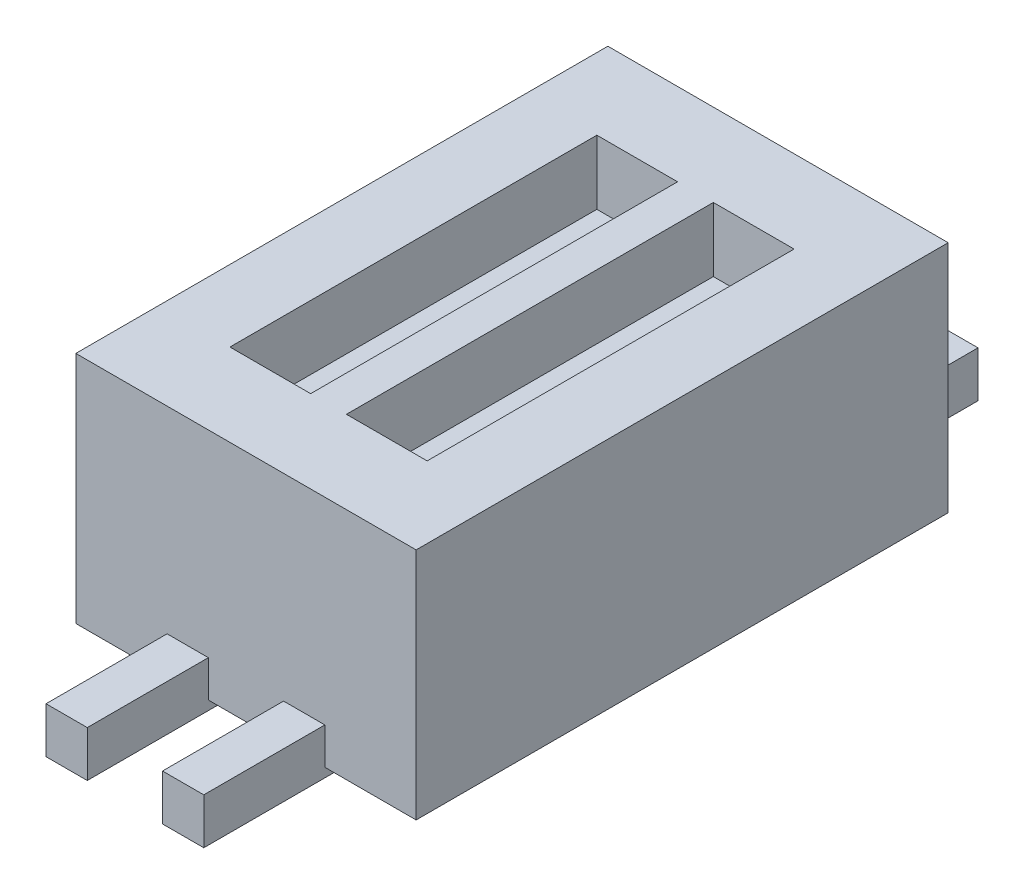
SolidWorks part; units mm, degrees
ref_plane "Front Plane" through (0, 0, 0) normal (0, 0, 1) x (1, 0, 0)
ref_plane "Top Plane" through (0, 0, 0) normal (0, 1, 0) x (1, 0, 0)
ref_plane "Right Plane" through (0, 0, 0) normal (1, 0, 0) x (0, 0, -1)
sketch "Sketch1" plane through (0, 0, 0) normal (0, 1, 0) x (1, 0, 0)
  line L1 (-1.855, 2.9) -> (1.855, 2.9)
  line L2 (-1.855, 2.9) -> (-1.855, -2.9)
  line L3 (-1.855, -2.9) -> (1.855, -2.9)
  line L4 (1.855, 2.9) -> (1.855, -2.9)
  line L5 (-1.855, 2.9) -> (1.855, -2.9) construction
  line L6 (-1.855, -2.9) -> (1.855, 2.9) construction
  point P0 (0, 0)
  dimension "D1" = 5.8
  dimension "D2" = 3.71
extrude "Boss-Extrude1" add sketch "Sketch1" along normal blind 2.55 from offset 0.1
sketch "Sketch2" plane through (0, 0, 0) normal (0, 1, 0) x (1, 0, 0)
  line L0 (-0.635, -3.31) -> (0.635, -3.31) construction
  line L1 (0.41, -2.4) -> (0.86, -2.4)
  line L2 (0.41, -2.4) -> (0.41, -4.22)
  line L3 (0.41, -4.22) -> (0.86, -4.22)
  line L4 (0.86, -2.4) -> (0.86, -4.22)
  line L5 (0.41, -2.4) -> (0.86, -4.22) construction
  line L6 (0.41, -4.22) -> (0.86, -2.4) construction
  line L7 (-0.86, -2.4) -> (-0.41, -2.4)
  line L8 (-0.86, -2.4) -> (-0.86, -4.22)
  line L9 (-0.86, -4.22) -> (-0.41, -4.22)
  line L10 (-0.41, -2.4) -> (-0.41, -4.22)
  line L11 (-0.86, -2.4) -> (-0.41, -4.22) construction
  line L12 (-0.86, -4.22) -> (-0.41, -2.4) construction
  line L13 (-1.855, -2.9) -> (1.855, -2.9) construction
  line L14 (-4.0772, 0) -> (4.7811, 0) construction
  line L15 (-0.86, 4.22) -> (-0.41, 2.4) construction
  line L16 (-0.86, 2.4) -> (-0.41, 4.22) construction
  line L17 (0.41, 4.22) -> (0.86, 2.4) construction
  line L18 (0.41, 2.4) -> (0.86, 4.22) construction
  line L19 (-0.635, 3.31) -> (0.635, 3.31) construction
  line L20 (-0.41, 2.4) -> (-0.41, 4.22)
  line L21 (-0.86, 4.22) -> (-0.41, 4.22)
  line L22 (-0.86, 2.4) -> (-0.86, 4.22)
  line L23 (-0.86, 2.4) -> (-0.41, 2.4)
  line L24 (0.86, 2.4) -> (0.86, 4.22)
  line L25 (0.41, 4.22) -> (0.86, 4.22)
  line L26 (0.41, 2.4) -> (0.41, 4.22)
  line L27 (0.41, 2.4) -> (0.86, 2.4)
  point P0 (0.635, -3.31)
  point P5 (-0.635, -3.31)
  point P12 (0, -3.31)
  point P28 (0, 3.31)
  dimension "D1" = 0.45
  dimension "D2" = 1.27
  dimension "D3" = 0.5
  dimension "D4" = 8.44
extrude "Boss-Extrude2" add sketch "Sketch2" along normal blind 0.5
sketch "Sketch3" plane through (0, 2.65, 0) normal (0, 1, 0) x (1, 0, 0)
  line L0 (-0.635, 0) -> (0.635, 0) construction
  line L1 (-1.075, 2) -> (-0.195, 2)
  line L2 (-1.075, 2) -> (-1.075, -2)
  line L3 (-1.075, -2) -> (-0.195, -2)
  line L4 (-0.195, 2) -> (-0.195, -2)
  line L5 (-1.075, 2) -> (-0.195, -2) construction
  line L6 (-1.075, -2) -> (-0.195, 2) construction
  line L7 (0.195, 2) -> (1.075, 2)
  line L8 (0.195, 2) -> (0.195, -2)
  line L9 (0.195, -2) -> (1.075, -2)
  line L10 (1.075, 2) -> (1.075, -2)
  line L11 (0.195, 2) -> (1.075, -2) construction
  line L12 (0.195, -2) -> (1.075, 2) construction
  point P0 (-0.635, 0)
  point P5 (0.635, 0)
  dimension "D1" = 1.27
  dimension "D2" = 0.88
  dimension "D3" = 4
extrude "Cut-Extrude1" cut sketch "Sketch3" against normal blind 0.7
